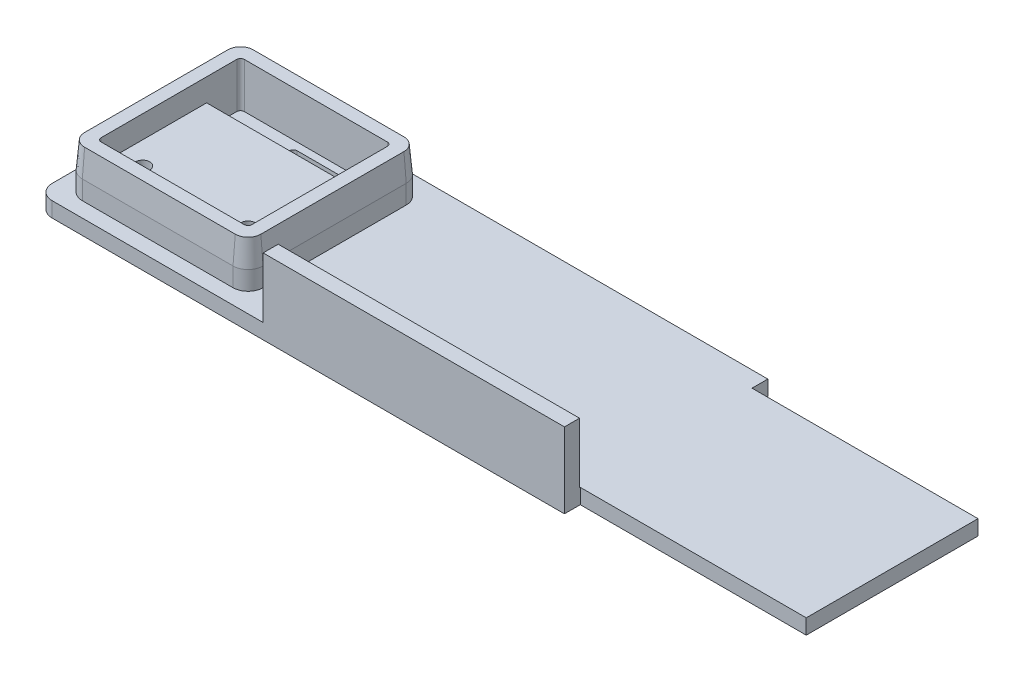
SolidWorks part; units mm, degrees
ref_plane "Front Plane" through (0, 0, 0) normal (0, 0, 1) x (1, 0, 0)
ref_plane "Top Plane" through (0, 0, 0) normal (0, 1, 0) x (1, 0, 0)
ref_plane "Right Plane" through (0, 0, 0) normal (1, 0, 0) x (0, 0, -1)
sketch "Sketch1" plane through (0, 0, 0) normal (0, 1, 0) x (1, 0, 0)
  line L1 (-14, -13.5) -> (14, -13.5)
  line L2 (-14, -13.5) -> (-14, 13.5)
  line L3 (-14, 13.5) -> (14, 13.5)
  line L4 (14, -13.5) -> (14, 13.5)
  line L5 (-14, -13.5) -> (14, 13.5) construction
  line L6 (-14, 13.5) -> (14, -13.5) construction
  point P0 (0, 0)
  dimension "D1" = 28
  dimension "D2" = 27
extrude "Boss-Extrude1" add sketch "Sketch1" along normal blind 2
sketch "Sketch2" plane through (0, 2, 0) normal (0, 1, 0) x (1, 0, 0)
  line L0 (14, 13.5) -> (-14, 13.5) construction
  line L1 (-2, 6) -> (8, 6)
  line L2 (-2, 6) -> (-2, 8.5)
  line L3 (-2, 8.5) -> (8, 8.5)
  line L4 (8, 6) -> (8, 8.5)
  line L5 (-2, 6) -> (8, 8.5) construction
  line L6 (-2, 8.5) -> (8, 6) construction
  line L7 (14, -13.5) -> (14, 13.5) construction
  point P0 (3, 7.25)
  dimension "D1" = 10
  dimension "D2" = 2.5
  dimension "D3" = 5
  dimension "D4" = 6
extrude "Cut-Extrude1" cut sketch "Sketch2" against normal up to surface (2 mm away) up to face at (0, 0, 0)
sketch "Sketch3" plane through (0, 2, 0) normal (0, 1, 0) x (1, 0, 0)
  line L0 (-10, -9.5) -> (10, -9.5)
  line L1 (10, -9.5) -> (10, 5)
  line L2 (10, 5) -> (-10, 5)
  line L3 (0, 13.5) -> (0, -13.5) construction
  line L4 (14, 13.5) -> (-14, 13.5) construction
  line L5 (-14, -13.5) -> (14, -13.5) construction
  line L7 (-2, 6) -> (8, 6) construction
  line L8 (-10, -9.5) -> (-10, 5)
  line L10 (14, -13.5) -> (14, 13.5) construction
  point P17 (0, -9.5)
  point P18 (0, 5)
  dimension "D1" = 4
  dimension "D2" = 4
  dimension "D3" = 1
extrude "Boss-Extrude2" add sketch "Sketch3" along normal blind 3
sketch "Sketch4" plane through (0, 2, 0) normal (0, 1, 0) x (1, 0, 0)
  line L0 (12, 11.5) -> (12, -11.5)
  line L1 (12, -11.5) -> (-12, -11.5)
  line L2 (-12, -11.5) -> (-12, 11.5)
  line L3 (-12, 11.5) -> (12, 11.5)
  line L4 (-10, -9.5) -> (-10, 9.5)
  line L5 (-10, 9.5) -> (10, 9.5)
  line L6 (10, 9.5) -> (10, -9.5)
  line L7 (10, -9.5) -> (-10, -9.5)
  line L8 (14, 13.5) -> (-14, 13.5) construction
  dimension "D1" = 2
  dimension "D2" = 2
  dimension "D3" = 2
  dimension "D4" = 2
  dimension "D5" = 2
extrude "Boss-Extrude3" add sketch "Sketch4" along normal blind 6
sketch "Sketch5" plane through (0, 5, 0) normal (0, 1, 0) x (1, 0, 0)
  line L0 (0, 5) -> (0, -9.5) construction
  line L1 (10, 5) -> (-10, 5) construction
  line L2 (-10, -9.5) -> (10, -9.5) construction
  circle A0 centre (-7, -6.5) radius 0.95
  circle A1 centre (7, -6.5) radius 0.95
  dimension "D3" = 1.9
  dimension "D1" = 7
  dimension "D2" = 3
extrude "Cut-Extrude2" cut sketch "Sketch5" against normal blind 3.2
fillet "Fillet3" radius 2 6 edges at (-14, 1, -13.5) (-14, 1, 13.5) (12, 5, -11.5) (12, 5, 11.5) (-12, 5, 11.5) (-12, 5, -11.5)
fillet "Fillet2" radius 0.5 8 edges at (-10, 6.5, 9.5) (10, 6.5, 9.5) (10, 5, -9.5) (-10, 5, -9.5) (-2, 1, -6) (-2, 1, -8.5) (8, 1, -8.5) (8, 1, -6)
sketch "Sketch6" plane through (14, 0, 0) normal (1, 0, 0) x (0, 0, -1)
  line L1 (-13.5, 0) -> (13.5, 0)
  line L2 (-13.5, 0) -> (-13.5, 2)
  line L3 (-13.5, 2) -> (13.5, 2)
  line L4 (13.5, 0) -> (13.5, 2)
extrude "Boss-Extrude4" add sketch "Sketch6" along normal blind 72
chamfer "Chamfer1" distance 3.5 angle 5 8 edges at (0, 8, -11.5) (-11.4142, 8, -10.9142) (11.4142, 8, -10.9142) (-12, 8, 0) (12, 8, 0) (-11.4142, 8, 10.9142) (11.4142, 8, 10.9142) (0, 8, 11.5)
sketch "Sketch7" plane through (0, 2, 0) normal (0, 1, 0) x (1, 0, 0)
  line L0 (86, 13.5) -> (86, -13.5) construction
  line L1 (86, 13.5) -> (56, 13.5)
  line L2 (86, 13.5) -> (86, 11.4)
  line L3 (86, 11.4) -> (56, 11.4)
  line L4 (56, 13.5) -> (56, 11.4)
  dimension "D1" = 2.1
  dimension "D2" = 30
extrude "Cut-Extrude3" cut sketch "Sketch7" against normal through all
mirror "Mirror1" about plane through (0, 0, 0) normal (0, 0, 1) of "Cut-Extrude3"
sketch "Sketch8" plane through (0, 0, 13.5) normal (0, 0, 1) x (1, 0, 0)
  line L0 (56, 10) -> (56, 2)
  line L2 (56, 10) -> (16, 10)
  line L3 (16, 10) -> (16, 2)
  line L4 (-12, 2) -> (56, 2) construction
  line L5 (16, 2) -> (56, 2)
  line L6 (12, 4.5) -> (12, 2) construction
  dimension "D1" = 4
  dimension "8" = 8
extrude "Boss-Extrude5" add sketch "Sketch8" against normal blind 2
